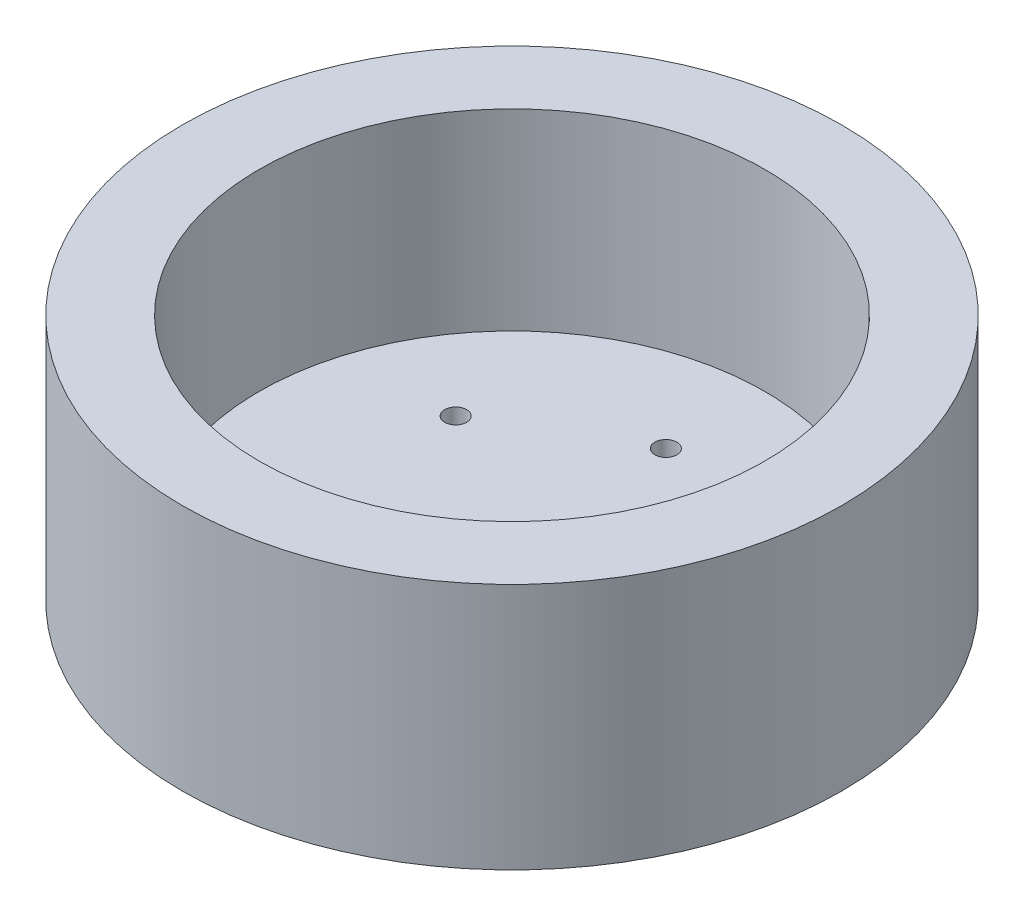
SolidWorks part; units mm, degrees
ref_plane "Front Plane" through (0, 0, 0) normal (0, 0, 1) x (1, 0, 0)
ref_plane "Top Plane" through (0, 0, 0) normal (0, 1, 0) x (1, 0, 0)
ref_plane "Right Plane" through (0, 0, 0) normal (1, 0, 0) x (0, 0, -1)
sketch "Sketch1" plane through (0, 0, 0) normal (0, 1, 0) x (1, 0, 0)
  circle A0 centre (0, 0) radius 28 construction
  circle A1 centre (0, 0) radius 60
  circle A2 centre (0, 28) radius 2
  circle A3 centre (24.2487, 14) radius 2
  circle A4 centre (24.2487, -14) radius 2
  circle A5 centre (0, -28) radius 2
  circle A6 centre (-24.2487, -14) radius 2
  circle A7 centre (-24.2487, 14) radius 2
  point P18 (0, 0)
  dimension "D1" = 56
  dimension "D2" = 120
  dimension "D3" = 4
  dimension "D4" = 6
extrude "Boss-Extrude1" add sketch "Sketch1" along normal blind 10
sketch "Sketch2" plane through (0, 10, 0) normal (0, 1, 0) x (1, 0, 0)
  circle A0 centre (0, 0) radius 46
  circle A1 centre (0, 0) radius 60 construction
  circle A2 centre (0, 0) radius 60
  dimension "D1" = 92
extrude "Boss-Extrude2" add sketch "Sketch2" along normal blind 35
